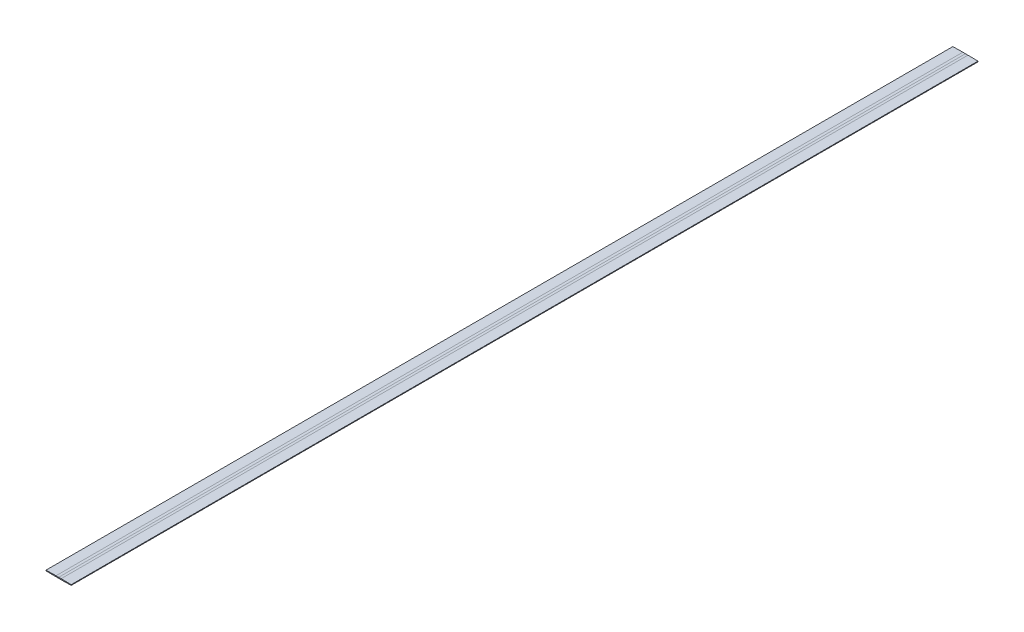
SolidWorks part; units mm, degrees
ref_plane "Front" through (0, 0, 0) normal (0, 0, 1) x (1, 0, 0)
ref_plane "Top" through (0, 0, 0) normal (0, 1, 0) x (1, 0, 0)
ref_plane "Right" through (0, 0, 0) normal (1, 0, 0) x (0, 0, -1)
sketch "Sketch1" plane through (0, 0, 0) normal (0, 0, 1) x (1, 0, 0)
  line L0 (-25.4, -0.6604) -> (-5.1594, -0.9906)
  line L1 (-5.1594, -0.9906) -> (0, -0.7937)
  line L2 (0, -0.7937) -> (0, 0)
  line L3 (0, 0) -> (-25.4, 0)
  line L4 (-25.4, 0) -> (-25.4, -0.6604)
  line L5 (0, 0) -> (0, 5.8145) construction
  line L6 (0, 0) -> (5.1284, 0) construction
  dimension "D1" = 1.3208
  dimension "Middle Th" = 1.5875
  dimension "Middle Width" = 10.3187
  dimension "wd" = 50.8
  dimension "Leaf Th" = 1.9812
extrude "Extrude1" add sketch "Sketch1" along normal mid plane 1828.8
mirror "Mirror1" about plane through (0, 0, 0) normal (1, 0, 0) of "Extrude1"
mirror "Mirror2" about plane through (0, 0, 0) normal (0, 1, 0) of "Mirror1", "Extrude1"
sketch "Sketch2" plane through (0, 0, 0) normal (0, 0, 1) x (1, 0, 0)
  line L0 (-25.4, 0.6604) -> (-25.4, -0.6604) construction
  point P0 (-25.4, 0.9906)
  point P1 (-25.4, -0.9906)
equation "\"D1@Sketch1\" = \"Leaf Th@Sketch1\"/1.5"
